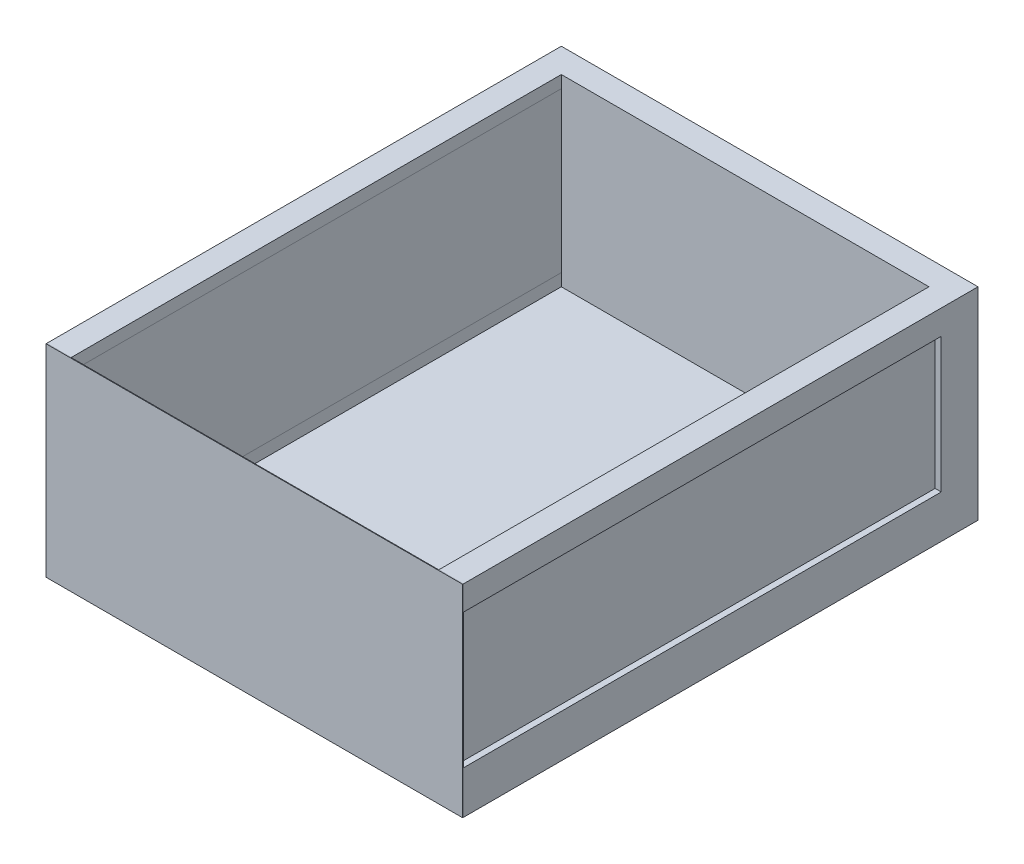
SolidWorks part; units mm, degrees
ref_plane "Front Plane" through (0, 0, 0) normal (0, 0, 1) x (1, 0, 0)
ref_plane "Top Plane" through (0, 0, 0) normal (0, 1, 0) x (1, 0, 0)
ref_plane "Right Plane" through (0, 0, 0) normal (1, 0, 0) x (0, 0, -1)
sketch "Sketch1" plane through (0, 0, 0) normal (0, 1, 0) x (1, 0, 0)
  line L1 (-34, 42) -> (34, 42)
  line L2 (-34, 42) -> (-34, -42)
  line L3 (-34, -42) -> (34, -42)
  line L4 (34, 42) -> (34, -42)
  line L5 (-34, 42) -> (34, -42) construction
  line L6 (-34, -42) -> (34, 42) construction
  point P0 (0, 0)
  dimension "D1" = 84
  dimension "D2" = 68
extrude "Boss-Extrude1" add sketch "Sketch1" along normal blind 3
sketch "Sketch2" plane through (0, 3, 0) normal (0, 1, 0) x (1, 0, 0)
  line L0 (-30, -42) -> (-34, -42)
  line L1 (34, -42) -> (30, -42)
  line L2 (34, -42) -> (34, 42)
  line L3 (34, 42) -> (-34, 42)
  line L4 (-34, -42) -> (-34, 42)
  line L5 (34, -42) -> (-34, 42) construction
  line L6 (34, 42) -> (-34, -42) construction
  line L7 (-30, 38) -> (30, 38)
  line L8 (-30, 38) -> (-30, -42)
  line L10 (30, 38) -> (30, -42)
  point P0 (0, 0)
  dimension "D1" = 4
  dimension "D2" = 4
  dimension "D3" = 4
extrude "Boss-Extrude2" add sketch "Sketch2" along normal blind 30
sketch "Sketch3" plane through (-34, 0, 0) normal (-1, 0, 0) x (0, 0, 1)
  line L0 (-42, 33) -> (42, 33) construction
  line L1 (-36, 29) -> (42, 29)
  line L2 (-36, 29) -> (-36, 7)
  line L3 (-36, 7) -> (42, 7)
  line L4 (42, 29) -> (42, 7)
  line L5 (42, 3) -> (-38, 3) construction
  line L6 (-42, 33) -> (-42, 0) construction
  line L7 (42, 33) -> (42, 0) construction
  dimension "D1" = 4
  dimension "D2" = 4
  dimension "D3" = 6
  dimension "D4" = 0
extrude "Cut-Extrude1" cut sketch "Sketch3" against normal blind 1
sketch "Sketch4" plane through (-30, 0, 0) normal (1, 0, 0) x (0, 0, -1)
  line L0 (-42, 33) -> (38, 33) construction
  line L1 (-42, 31) -> (38, 31)
  line L2 (-42, 31) -> (-42, 5)
  line L3 (-42, 5) -> (38, 5)
  line L4 (38, 31) -> (38, 5)
  line L5 (-42, 33) -> (-42, 3) construction
  line L6 (-42, 3) -> (38, 3) construction
  line L7 (38, 33) -> (38, 3) construction
  dimension "D1" = 2
  dimension "D2" = 0
  dimension "D3" = 2
  dimension "D4" = 0
extrude "Cut-Extrude2" cut sketch "Sketch4" against normal blind 3
sketch "Sketch5" plane through (30, 0, 0) normal (-1, 0, 0) x (0, 0, 1)
  line L0 (42, 33) -> (-42, 33) construction
  line L1 (42, 31) -> (-38, 31)
  line L2 (42, 31) -> (42, 5)
  line L3 (42, 5) -> (-38, 5)
  line L4 (-38, 31) -> (-38, 5)
  line L6 (-38, 3) -> (42, 3) construction
  line L7 (42, 33) -> (42, 3) construction
  line L8 (-38, 33) -> (-38, 3) construction
  dimension "D1" = 2
  dimension "D2" = 0
  dimension "D3" = 2
  dimension "D4" = 0
extrude "Cut-Extrude3" cut sketch "Sketch5" against normal blind 3
sketch "Sketch7" plane through (34, 0, 0) normal (1, 0, 0) x (0, 0, -1)
  line L0 (38, 33) -> (-42, 33) construction
  line L1 (-42, 29) -> (36, 29)
  line L2 (-42, 29) -> (-42, 7)
  line L3 (-42, 7) -> (36, 7)
  line L4 (36, 29) -> (36, 7)
  line L5 (38, 3) -> (-42, 3) construction
  line L6 (-42, 5) -> (-42, 31) construction
  line L7 (42, 33) -> (42, 0) construction
  dimension "D1" = 4
  dimension "D2" = 4
  dimension "D3" = 0
  dimension "D4" = 6
extrude "Cut-Extrude4" cut sketch "Sketch7" against normal blind 1
sketch "Sketch8" plane through (-30, 0, 0) normal (1, 0, 0) x (0, 0, -1)
  line L1 (38, 5) -> (-42, 5)
  line L2 (38, 5) -> (38, 31)
  line L3 (38, 31) -> (-42, 31)
  line L4 (-42, 5) -> (-42, 31)
  dimension "D1" = 80
  dimension "D2" = 26
extrude "Boss-Extrude4" add sketch "Sketch8" against normal blind 3 separate body
sketch "Sketch9" plane through (30, 0, 0) normal (-1, 0, 0) x (0, 0, 1)
  line L1 (-38, 31) -> (42, 31)
  line L2 (-38, 31) -> (-38, 5)
  line L3 (-38, 5) -> (42, 5)
  line L4 (42, 31) -> (42, 5)
  dimension "D1" = 80
  dimension "D2" = 26
extrude "Boss-Extrude5" add sketch "Sketch9" against normal blind 3 separate body
sketch "Sketch10" plane through (0, 0, 42) normal (0, 0, 1) x (1, 0, 0)
  line L1 (-34, 33) -> (34, 33)
  line L2 (-34, 33) -> (-34, 0)
  line L3 (-34, 0) -> (34, 0)
  line L4 (34, 33) -> (34, 0)
extrude "Boss-Extrude6" add sketch "Sketch10" along normal blind 0.1 separate body
